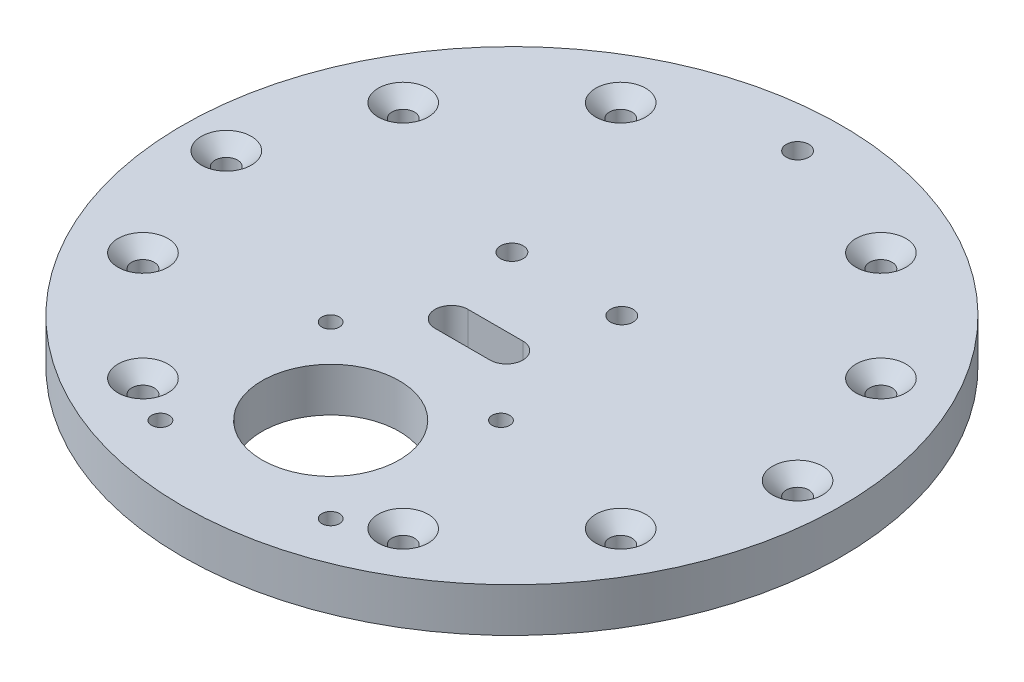
SolidWorks part; units mm, degrees
ref_plane "Front Plane" through (0, 0, 0) normal (0, 0, 1) x (1, 0, 0)
ref_plane "Top Plane" through (0, 0, 0) normal (0, 1, 0) x (1, 0, 0)
ref_plane "Right Plane" through (0, 0, 0) normal (1, 0, 0) x (0, 0, -1)
sketch "Sketch1" plane through (0, 0, 0) normal (0, 1, 0) x (1, 0, 0)
  circle A0 centre (0, 0) radius 60
  dimension "D1" = 120
extrude "Boss-Extrude1" add sketch "Sketch1" along normal blind 8
sketch "Sketch2" plane through (0, 8, 0) normal (0, 1, 0) x (1, 0, 0)
  line L1 (15.5, -48.5) -> (-15.5, -48.5) construction
  line L2 (15.5, -48.5) -> (15.5, -17.5) construction
  line L3 (15.5, -17.5) -> (-15.5, -17.5) construction
  line L4 (-15.5, -48.5) -> (-15.5, -17.5) construction
  line L5 (15.5, -48.5) -> (-15.5, -17.5) construction
  line L6 (15.5, -17.5) -> (-15.5, -48.5) construction
  circle A0 centre (0, -33) radius 12.5
  circle A1 centre (-15.5, -48.5) radius 1.6
  circle A2 centre (15.5, -48.5) radius 1.6
  circle A3 centre (15.5, -17.5) radius 1.6
  circle A4 centre (-15.5, -17.5) radius 1.6
  dimension "D1" = 25
  dimension "D5" = 3.2
  dimension "D6" = 3.2
  dimension "D7" = 3.2
  dimension "D8" = 3.2
  dimension "D2" = 33
  dimension "D3" = 31
  dimension "D4" = 31
extrude "Cut-Extrude1" cut sketch "Sketch2" against normal through all
sketch "Sketch3" plane through (0, 8, 0) normal (0, 1, 0) x (1, 0, 0)
  line L0 (0, 0) -> (0, -60) construction
  line L1 (0, 0) -> (-33.5876, -33.5876) construction
  line L2 (-9.8995, 9.8995) -> (-43.4871, -23.6881) construction
  line L3 (9.8995, -9.8995) -> (-23.6881, -43.4871) construction
  circle A0 centre (0, 0) radius 60 construction
  circle A1 centre (-33.5876, -33.5876) radius 5 construction
  circle A2 centre (-43.4871, -23.6881) radius 2.05
  circle A3 centre (-23.6881, -43.4871) radius 2.05
  dimension "D5" = 4.1
  dimension "D6" = 4.1
  dimension "D7" = 10
  dimension "D1" = 45
  dimension "D2" = 47.5
  dimension "D3" = 14
  dimension "D4" = 14
extrude "Cut-Extrude2" cut sketch "Sketch3" against normal through all contours A2 | A3
pattern_circular "CirPattern1" count 4 over 360 about axis through (0, 0, 0) along (0, 1, 0) of "Cut-Extrude2"
sketch "Sketch4" plane through (0, 8, 0) normal (0, 1, 0) x (1, 0, 0)
  circle A0 centre (-52, 0) radius 2.05
  circle A1 centre (52, 0) radius 2.05
  circle A2 centre (0, 52) radius 2.05
  dimension "D3" = 4.1
  dimension "D4" = 4.1
  dimension "D6" = 4.1
  dimension "D1" = 52
  dimension "D2" = 52
  dimension "D5" = 52
extrude "Cut-Extrude3" cut sketch "Sketch4" against normal through all
sketch "Sketch5" plane through (0, 8, 0) normal (0, 1, 0) x (1, 0, 0)
  line L0 (-5, -6) -> (5, -6) construction
  line L1 (-5, -3) -> (5, -3)
  line L2 (-5, -9) -> (5, -9)
  circle A0 centre (-10, 10) radius 2.05
  circle A1 centre (10, 10) radius 2.05
  arc A2 (-5, -3) -> (-5, -9) centre (-5, -6) ccw
  arc A3 (5, -9) -> (5, -3) centre (5, -6) ccw
  point P6 (0, -6)
  dimension "D1" = 3
  dimension "D2" = 4.1
  dimension "D3" = 4.1
  dimension "D4" = 13
  dimension "D5" = 3
  dimension "D6" = 10
  dimension "D7" = 10
  dimension "D8" = 10
extrude "Cut-Extrude4" cut sketch "Sketch5" against normal through all
sketch "Sketch6" plane through (0, 0, 0) normal (0, -1, 0) x (1, 0, 0)
  line L1 (0, -38) -> (8, -38)
  line L2 (0, -38) -> (0, -18)
  line L3 (0, -18) -> (8, -18)
  line L4 (8, -38) -> (8, -18)
  line L5 (0, -38) -> (8, -18) construction
  line L6 (0, -18) -> (8, -38) construction
  point P0 (4, -28)
  dimension "D1" = 20
  dimension "D2" = 8
  dimension "D3" = 18
extrude "Boss-Extrude2" add sketch "Sketch6" along normal blind 18 contours L3 L4 L1 L2
chamfer "Chamfer1" distance 5 angle 45 1 edges at (8, 0, -28)
sketch "Sketch7" plane through (8, 0, 0) normal (1, 0, 0) x (0, 0, -1)
  line L0 (38, -18) -> (18, -18) construction
  line L1 (38, -18) -> (38, -5) construction
  circle A0 centre (23.25, -10.5) radius 1.6
  circle A1 centre (32.75, -10.5) radius 1.6
  dimension "D1" = 7.5
  dimension "D2" = 3.2
  dimension "D3" = 3.2
  dimension "D4" = 9.5
  dimension "D5" = 5.25
extrude "Cut-Extrude5" cut sketch "Sketch7" against normal through all
hole_wizard "CSK for M4 Countersunk Flat Head Screw1" positions "3DSketch1" profile "Sketch9" countersink size "M4" standard "ISO"
sketch3d "3DSketch1"
  line L0 (-52, 0, 0) -> (-52, 8, 0) construction
  line L1 (-43.4871, 0, 23.6881) -> (-43.4871, 8, 23.6881) construction
  line L2 (-23.6881, 0, 43.4871) -> (-23.6881, 8, 43.4871) construction
  line L3 (23.6881, 0, 43.4871) -> (23.6881, 8, 43.4871) construction
  line L4 (43.4871, 0, 23.6881) -> (43.4871, 8, 23.6881) construction
  line L5 (52, 0, 0) -> (52, 8, 0) construction
  line L6 (43.4871, 0, -23.6881) -> (43.4871, 8, -23.6881) construction
  line L7 (23.6881, 0, -43.4871) -> (23.6881, 8, -43.4871) construction
  line L8 (-23.6881, 0, -43.4871) -> (-23.6881, 8, -43.4871) construction
  line L9 (-43.4871, 0, -23.6881) -> (-43.4871, 8, -23.6881) construction
  point P0 (-52, 8, 0)
  point P4 (-43.4871, 8, 23.6881)
  point P8 (-23.6881, 8, 43.4871)
  point P12 (23.6881, 8, 43.4871)
  point P16 (43.4871, 8, 23.6881)
  point P20 (52, 8, 0)
  point P24 (43.4871, 8, -23.6881)
  point P28 (23.6881, 8, -43.4871)
  point P32 (-23.6881, 8, -43.4871)
  point P36 (-43.4871, 8, -23.6881)
sketch "Sketch9" plane through (-52, 8, 0) normal (1, 0, 0) x (0, 0, 1)
  line L0 (0, 0) -> (0, 9.2308)
  line L1 (0, 9.2308) -> (2.05, 7.999)
  line L2 (2.05, 7.999) -> (2.05, 2.5)
  line L3 (2.05, 2.5) -> (4.55, 0)
  line L5 (4.55, 0) -> (0, 0)
  line L6 (-2.05, 2.5) -> (-4.55, 0) construction
  line L10 (0, 9.2308) -> (-2.05, 7.999) construction
  line L11 (0, -6.35) -> (0, 107.95) construction
  dimension "Hole Dia." = 4.1
  dimension "Hole Depth" = 7.999
  dimension "Near C'Sink Dia." = 9.1
  dimension "Near C'Sink Angle" = 90
  dimension "Drill Angle" = 118
